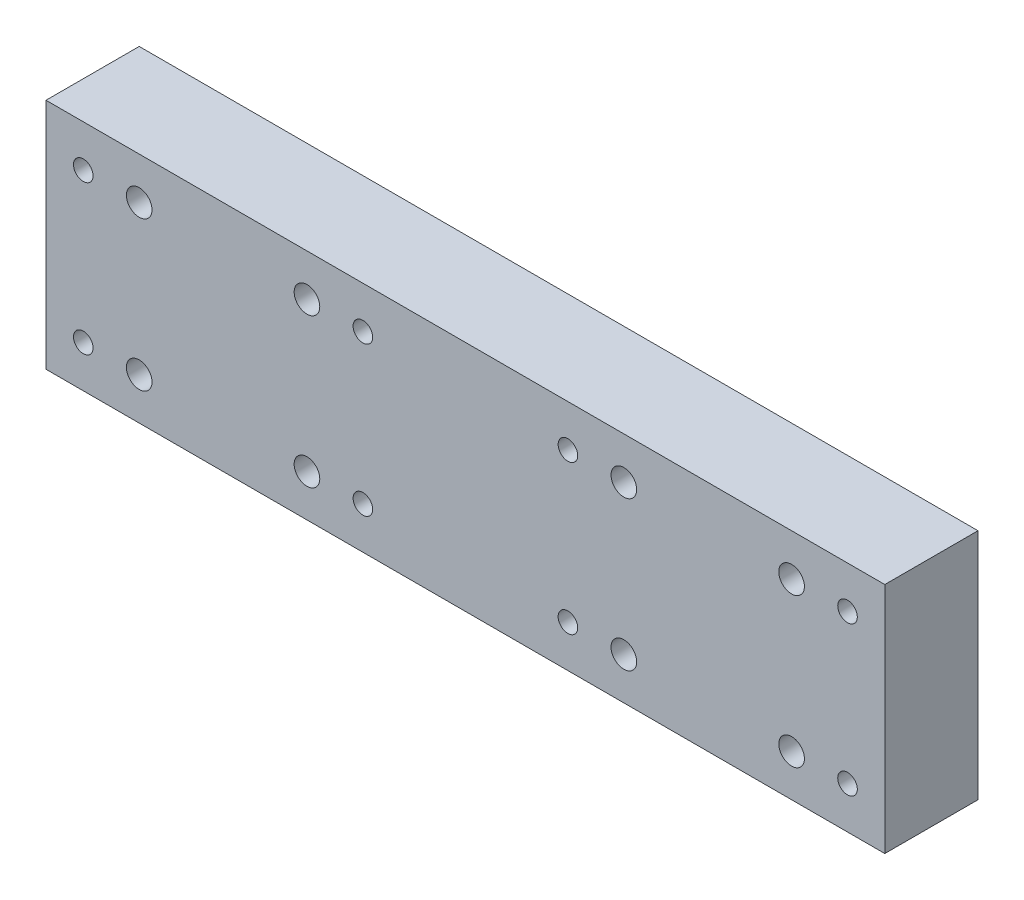
SolidWorks part; units mm, degrees
material "3.3545 (EN-AW 5086)"
ref_plane "Ebene vorne" through (0, 0, 0) normal (0, 0, 1) x (1, 0, 0)
ref_plane "Ebene oben" through (0, 0, 0) normal (0, 1, 0) x (1, 0, 0)
ref_plane "Ebene rechts" through (0, 0, 0) normal (1, 0, 0) x (0, 0, -1)
sketch "Skizze1" plane through (0, 0, 0) normal (0, 0, 1) x (1, 0, 0)
  line L0 (0, 0) -> (0, 306.9421) construction
  line L1 (-90, 0) -> (90, 0)
  line L2 (-90, 0) -> (-90, 50)
  line L3 (-90, 50) -> (90, 50)
  line L4 (90, 0) -> (90, 50)
  dimension "D1" = 50
  dimension "D2" = 180
extrude "Aufsatz-Linear austragen1" add sketch "Skizze1" along normal blind 20
sketch "Skizze2" plane through (0, 0, 20) normal (0, 0, 1) x (1, 0, 0)
  line L0 (0, 0) -> (0, 63.307) construction
  line L1 (0, 25) -> (97.4425, 25) construction
  line L2 (34, 9) -> (70, 9) construction
  line L3 (-90, 0) -> (90, 0) construction
  circle A0 centre (34, 9) radius 2.75
  circle A1 centre (70, 9) radius 2.75
  circle A2 centre (70, 41) radius 2.75
  circle A3 centre (34, 41) radius 2.75
  circle A4 centre (-34, 9) radius 2.75
  circle A5 centre (-70, 9) radius 2.75
  circle A6 centre (-70, 41) radius 2.75
  circle A7 centre (-34, 41) radius 2.75
  dimension "D1" = 68
  dimension "D2" = 36
  dimension "D3" = 32
  dimension "D5" = 5.5
  dimension "D4" = 9
extrude "Schnitt-Linear austragen1" cut sketch "Skizze2" against normal blind 40
sketch "Skizze3" plane through (0, 0, 0) normal (0, 0, 1) x (1, 0, 0)
  circle A0 centre (-70, 41) radius 5
  circle A1 centre (-34, 41) radius 5
  circle A2 centre (34, 41) radius 5
  circle A3 centre (70, 41) radius 5
  circle A4 centre (70, 9) radius 5
  circle A5 centre (34, 9) radius 5
  circle A6 centre (-34, 9) radius 5
  circle A7 centre (-70, 9) radius 5
  dimension "D1" = 10
extrude "Schnitt-Linear austragen2" cut sketch "Skizze3" along normal blind 6
hole_wizard "Ø4.2 (4.2) Durchmesser Bohrung1" positions "Skizze4" profile "Skizze5" hole size "Ø4.2" standard "DIN"
sketch "Skizze4" plane through (0, 0, 0) normal (0, 0, -1) x (-1, 0, 0)
  line L0 (0, 0) -> (0, 50) construction
  line L4 (-90, 50) -> (90, 50) construction
  line L5 (0, 25) -> (90, 25) construction
  line L6 (90, 50) -> (90, 0) construction
  line L7 (70, 41) -> (82, 41) construction
  line L8 (34, 41) -> (22, 41) construction
  point P20 (82, 41)
  point P29 (22, 41)
  point P40 (82, 9)
  point P41 (22, 9)
  point P43 (-82, 9)
  point P44 (-82, 41)
  point P45 (-22, 41)
  point P46 (-22, 9)
  dimension "D1" = 82
  dimension "D2" = 12
  dimension "D3" = 22
  dimension "D4" = 12
sketch "Skizze5" plane through (22, 9, 0) normal (1, 0, 0) x (0, 1, 0)
  line L0 (0, 0) -> (0, 35.2618)
  line L1 (0, 35.2618) -> (2.1, 34)
  line L2 (2.1, 34) -> (2.1, 0)
  line L5 (2.1, 0) -> (0, 0)
  line L10 (0, 35.2618) -> (-2.1, 34) construction
  line L11 (0, -6.35) -> (0, 107.95) construction
  dimension "Bohrerdurchmesser" = 4.2
  dimension "Bohrungstiefe" = 34
  dimension "Spitzenwinkel" = 118
